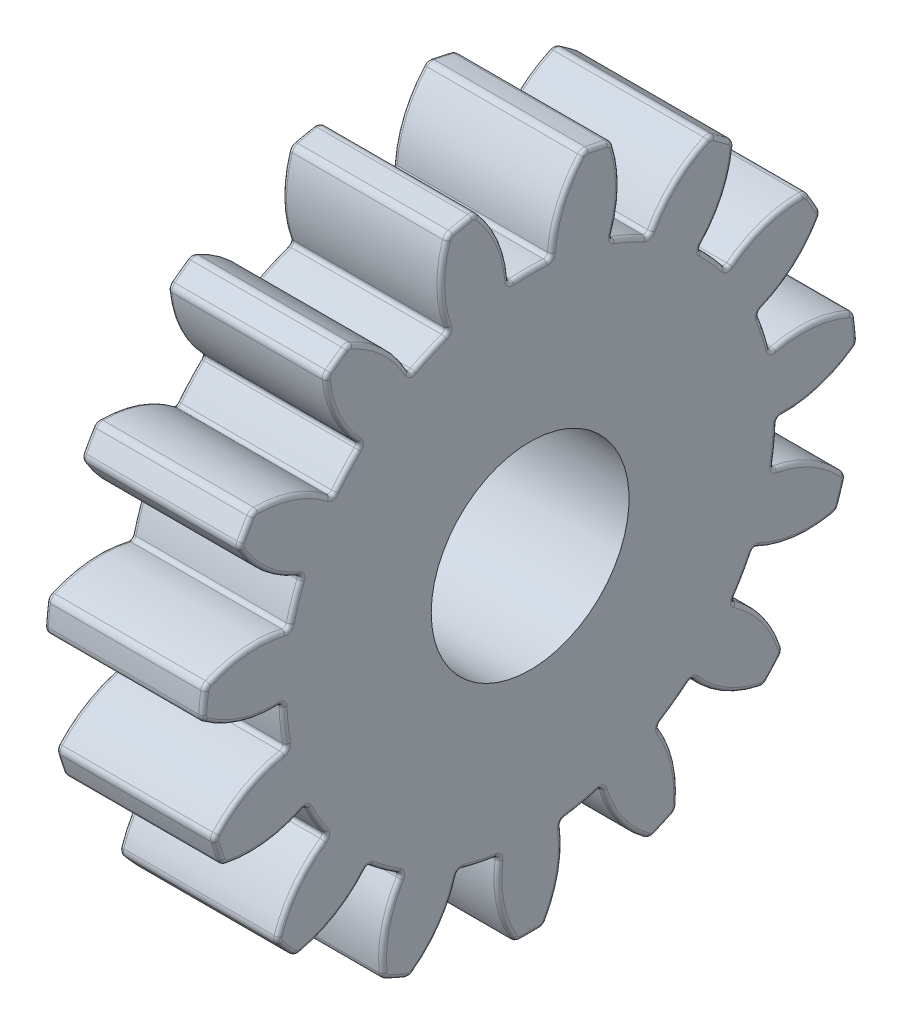
SolidWorks part; units mm, degrees
ref_plane "Plane1" through (0, 0, 0) normal (0, 0, 1) x (1, 0, 0)
ref_plane "Plane2" through (0, 0, 0) normal (0, 1, 0) x (1, 0, 0)
ref_plane "Plane3" through (0, 0, 0) normal (1, 0, 0) x (0, 0, -1)
sketch "HoldingSke" plane through (0, 0, 0) normal (0, 1, 0) x (1, 0, 0)
  line L0 (0, 0) -> (0.9659, -0.2588)
  line L1 (-15, 0) -> (100, 0) construction
  line L2 (0, 0) -> (-2.1039, 2.3779)
  line L3 (0, 0) -> (-11.863, 4.5341)
  line L4 (0, 0) -> (8.3417, 2.2352)
  line L5 (0, 0) -> (-46.8476, -17.4728)
  line L6 (0, 0) -> (-3.3159, -2.2372)
  line L7 (-2.1039, 2.3779) -> (8.6586, 51.2059)
  line L8 (-76.2, 54.61) -> (-75.3, 54.61)
  line L9 (-71.009, 38.7566) -> (-53.1078, 45.2721)
  line L10 (-76.2, 71.12) -> (104.1128, 71.12)
  line L11 (0, 0) -> (-4, 0)
  line L12 (-76.2, 101.6) -> (-76.162, 101.6)
  line L13 (24.9733, 27.94) -> (52.9518, 28.4284)
  line L14 (24.9733, 27.94) -> (24.9743, 27.94)
  line L15 (24.9733, 27.94) -> (100.4006, 29.5858)
  line L16 (-63.627, -1) -> (-12.827, -1)
  circle A0 centre (0, 0) radius 2.5
  circle A1 centre (0, 0) radius 6.249
  circle A2 centre (0, 0) radius 37.5
  circle A3 centre (0, 0) radius 2.5
  dimension "MHD" = 12.498
  dimension "Hub_dia" = 75
  dimension "Bore" = 5
  dimension "MBD" = 5
  dimension "Num_teeth" = 15
  dimension "Pitch" = 1
  dimension "Overall_len" = 50
  dimension "Show_teeth" = 15
  dimension "Thickness" = 4
  dimension "OAL" = 50.0001
  dimension "T_dim" = 0.9
  dimension "Ap" = 20
  dimension "H" = 19.05
  dimension "Pitch_radius" = 180.3128
  dimension "Width" = 4
  dimension "Backlash" = 0.038
  dimension "Addendum_fac" = 1
  dimension "Dedendum_fac" = 1.25
  dimension "Clearance_fac" = 0.25
  dimension "Dedendum_add" = 0.001
  dimension "Module" = 1
sketch "BasProSke" plane through (0, 0, 0) normal (0, 1, 0) x (1, 0, 0)
  line L0 (-10, 0) -> (60, 0) construction
  line L1 (0, 0) -> (0, 8.5)
  line L2 (0, 0) -> (4, 0)
  line L3 (4, 0) -> (4, 8.5)
  line L4 (4, 8.5) -> (0, 8.5)
  dimension "Thickness" = 4
  dimension "Diameter" = 17
revolve "Base-Revolve" add sketch "BasProSke" angle 360 about L0
sketch "TooCutSke" plane through (0, 0, 0) normal (1, 0, 0) x (0, 0, -1)
  line L1 (0, 0) -> (0, 107) construction
  line L2 (0, 0) -> (-0.8504, 7.4516) construction
  line L3 (0, 0) -> (-3.1044, 14.6049) construction
  line L4 (-0.8504, 7.4516) -> (-1.5522, 7.3025) construction
  arc A0 (0.5316, 6.2263) -> (-0.5316, 6.2263) centre (0, 0) ccw
  arc A1 (1.5766, 8.3784) -> (-1.5766, 8.3784) centre (0, 0) ccw
  circle A2 centre (0, 0) radius 7.5 construction
  circle A3 centre (0, 0) radius 7.0477 construction
  arc A4 (-0.5316, 6.2263) -> (-1.5766, 8.3784) centre (-3.5289, 6.1005) ccw
  arc A5 (1.5766, 8.3784) -> (0.5316, 6.2263) centre (3.5289, 6.1005) ccw
  dimension "Root_dia" = 12.498
  dimension "Overcut_dia" = 17.0508
  dimension "Pitch_dia" = 15
  dimension "Base_dia" = 14.0954
  dimension "Flank_rad" = 3
  dimension "Half_ang" = 12
  dimension "Half_CT" = 0.7175
extrude "ToothCut" cut sketch "TooCutSke" along normal through all
fillet "Breaks" [suppressed] radius 0.02
fillet "RootFillets" [suppressed] radius 0.251
pattern_circular "TeethCuts" count 15 every 24 about axis through (-10, 0, 0) along (1, 0, 0) of "ToothCut", "RootFillets", "Breaks"
sketch "HubNeaOneSke" plane through (0, 0, 0) normal (-1, 0, 0) x (0, 0, 1)
  circle A0 centre (0, 0) radius 6.249
  dimension "Diameter" = 12.498
extrude "HubNearOne" [suppressed] add sketch "HubNeaOneSke" along normal blind 46.0001
sketch "HubNeaBotSke" plane through (0, 0, 0) normal (-1, 0, 0) x (0, 0, 1)
  circle A0 centre (0, 0) radius 6.249
  dimension "Diameter" = 12.498
extrude "HubNearBoth" [suppressed] add sketch "HubNeaBotSke" along normal blind 23
ref_plane "FarPln" through (4, 0, 0) normal (1, 0, 0) x (0, 0, -1)
sketch "HubFarSke" plane through (4, 0, 0) normal (1, 0, 0) x (0, 0, -1)
  circle A0 centre (0, 0) radius 6.249
  dimension "Diameter" = 12.498
extrude "HubFar" [suppressed] add sketch "HubFarSke" along normal blind 23
sketch "BorSke" plane through (0, 0, 0) normal (1, 0, 0) x (0, 0, -1)
  circle A0 centre (0, 0) radius 2.5
  dimension "Diameter" = 5
extrude "Bore" cut sketch "BorSke" along normal mid plane 100.0001
sketch "KeySke" plane through (0, 0, 0) normal (1, 0, 0) x (0, 0, -1)
  line L0 (-1, 0) -> (-1, 3.4)
  line L1 (-1, 3.4) -> (1, 3.4)
  line L2 (1, 3.4) -> (1, 0)
  line L3 (0, 0) -> (0, 34) construction
  line L4 (-1, 0) -> (1, 0)
  dimension "Offset" = 3.4
  dimension "Width" = 2
extrude "Keyway" [suppressed] cut sketch "KeySke" along normal mid plane 100.0001
pattern_circular "Keyway2" [suppressed] count 2 every 90 about axis through (-10, 0, 0) along (1, 0, 0)
sketch "Sketch1" plane through (4, 0, 0) normal (1, 0, 0) x (0, 0, -1)
  circle A0 centre (0, 0) radius 8.3
  dimension "D1" = 16.6
extrude "Cut-Extrude1" cut sketch "Sketch1" against normal blind 10 flip side to cut
fillet "Fillet1" radius 0.2 30 edges at (2, -7.429, 3.7014) (2, -5.2812, 6.403) (2, -2.9046, 7.7752) (2, -5.8159, 5.9216) (2, -7.7216, 3.0441) (2, -8.2922, -0.3598) (2, -8.2922, 0.3598) (2, -7.7216, -3.0441) (2, -7.429, -3.7014) (2, -5.8159, -5.9216) (2, -5.2812, -6.403) (2, -2.9046, -7.7752) (2, -2.2203, -7.9975) (2, 0.509, -8.2844) (2, 1.2246, -8.2092) (2, 6.92, -4.583) (2, 6.4971, -5.1651) (2, 3.8345, -7.3611) (2, 4.4577, -7.0014) (2, -2.2203, 7.9975) (2, 0.509, 8.2844) (2, 1.2246, 8.2092) (2, 3.8345, 7.3611) (2, 4.4577, 7.0014) (2, 6.4971, 5.1651) (2, 6.92, 4.583) (2, 8.0362, 2.0759) (2, 8.1858, 1.3722) (2, 8.1858, -1.3722) (2, 8.0362, -2.0759)
fillet "Fillet2" radius 0.1 80 edges at (4, -3.1245, 5.4118) (0, 0.5193, -8.2589) (0, 0.8676, -8.2545) (0, 1.2092, -8.1864) (4, 0.8676, -8.2545) (0, 2.9482, -6.6457) (0, 3.8336, -7.3336) (0, 4.4343, -6.9868) (4, 3.8336, -7.3336) (4, 4.15, -7.188) (4, 4.4343, -6.9868) (4, 6.485, -5.1404) (0, 6.9115, -2.2559) (0, 8.0151, -2.0583) (0, 8.1186, -1.7257) (4, 6.9115, -2.2559) (4, 8.1186, -1.7257) (0, 8.1593, 1.3797) (0, 8.0151, 2.0583) (4, 8.1593, 1.3797) (4, 6.3011, 3.6267) (4, -1.5021, -7.1135) (4, -2.5648, -7.8938) (0, -2.2251, -7.9704) (0, -2.5648, -7.8938) (4, -5.2746, -6.3763) (4, -5.7901, -5.9122) (4, -6.2914, -3.6436) (0, -7.412, -3.6797) (0, -7.6942, -3.046) (4, -8.2679, -0.3468) (0, -8.3, 0) (4, -6.9175, 2.2374) (4, -7.6942, 3.046) (0, -7.5824, 3.3759) (0, -7.412, 3.6797) (0, -1.5021, 7.1135) (0, -2.2251, 7.9704) (0, -2.8848, 7.7561) (4, -1.5021, 7.1135) (4, -2.5648, 7.8938) (0, 0.5193, 8.2589) (4, 1.2092, 8.1864) (0, 4.15, 7.188) (4, 4.4343, 6.9868) (4, 3.8336, 7.3336) (0, 6.7148, -4.8786) (0, 6.8927, 4.5791) (4, -0.6532, 6.2148) (2, -1.1795, 6.1367) (4, -6.1124, 1.2992) (0, -6.1124, 1.2992) (2, -4.7248, 4.0898) (4, -5.0555, 3.6731) (0, -5.0555, 3.6731) (4, -6.1124, -1.2992) (2, -5.3497, -3.2297) (4, -5.0555, -3.6731) (2, -3.5735, -5.1264) (4, -3.1245, -5.4118) (0, -3.1245, -5.4118) (4, 6.249, 0) (2, 6.2263, 0.5316) (0, 4.1814, 4.6439) (2, 5.4718, 3.0181) (2, 1.4185, -6.0859) (0, 1.5211, -7.1094) (4, 1.5211, -7.1094) (0, 4.2813, -5.8761) (4, 4.2813, -5.8761) (2, 5.4718, -3.0181) (0, 6.3011, -3.6267) (4, 6.9115, 2.2559) (0, -2.966, -6.6378) (0, -5.4094, -4.8576) (2, -6.2008, 0.7746) (4, -7.2295, 0.7696) (2, -5.3497, 3.2297) (2, -2.6528, 5.658) (4, -2.966, 6.6378)
equation "' \"Module@HoldingSke\" = 6.35"
equation "' \"Num_teeth@HoldingSke\" = 12"
equation "' \"Ap@HoldingSke\" =  20"
equation "' \"Ap@HoldingSke\" = 20"
equation "' \"Width@HoldingSke\" = 0.5 * 25.4"
equation "' \"Hub_dia@HoldingSke\"= 1 * 25.4"
equation "' \"Hub_dia@HoldingSke\" = 1 * 25.4"
equation "' \"Overall_len@HoldingSke\" = 1.0 * 25.4"
equation "' \"Bore@HoldingSke\" = 0.75 * 25.4"
equation "' \"T_dim@HoldingSke\" = 0.1 * 25.4"
equation "' \"Width@KeySke\" = 0.25 * 25.4"
equation "' \"Show_teeth@HoldingSke\" = 13"
equation "' \"Backlash@HoldingSke\" = 0.009 * 25.4"
equation "' \"Addendum_fac@HoldingSke\" = 1.0"
equation "' \"Dedendum_fac@HoldingSke\" = 1.25"
equation "' \"Dedendum_add@HoldingSke\" = 0.00005 * 25.4"
equation "' \"Clearance_fac@HoldingSke\" = 0.25"
equation "\"Pitch@HoldingSke\" = 1 / \"Module@HoldingSke\""
equation "\"Overcut_dia@TooCutSke\" = (\"Num_teeth@HoldingSke\" + 2 * \"Addendum_fac@HoldingSke\") / \"Pitch@HoldingSke\" + 0.002 * 25.4"
equation "\"Pitch_dia@TooCutSke\" = \"Num_teeth@HoldingSke\" / \"Pitch@HoldingSke\""
equation "\"Base_dia@TooCutSke\" = \"Num_teeth@HoldingSke\" / \"Pitch@HoldingSke\" * cos((\"Ap@HoldingSke\"  * 3.14159265 / 180))"
equation "\"Root_dia@TooCutSke\" = (\"Num_teeth@HoldingSke\" + 2) / \"Pitch@HoldingSke\" - 2 * (\"Addendum_fac@HoldingSke\" + \"Dedendum_fac@HoldingSke\") / \"Pitch@HoldingSke\" - \"Dedendum_add@HoldingSke\" * 2"
equation "\"Half_ang@TooCutSke\" = 180 / \"Num_teeth@HoldingSke\""
equation "\"Half_CT@TooCutSke\" = \"Num_teeth@HoldingSke\" / \"Pitch@HoldingSke\" * sin((3.14159265 / 2 / \"Num_teeth@HoldingSke\")) / 2 - 7 * \"Backlash@HoldingSke\" / 4"
equation "\"Flank_rad@TooCutSke\" = \"Num_teeth@HoldingSke\" / \"Pitch@HoldingSke\" / 5"
equation "\"Radius@RootFillets\" = \"Clearance_fac@HoldingSke\" / \"Pitch@HoldingSke\" + \"Dedendum_add@HoldingSke\""
equation "\"Break_rad@Breaks\" = 0.02 / \"Pitch@HoldingSke\""
equation "\"Thickness@HoldingSke\" = \"Width@HoldingSke\""
equation "\"OAL@HoldingSke\" = \"Thickness@HoldingSke\""
equation "\"MHD@HoldingSke\" = (\"Num_teeth@HoldingSke\" + 2) / \"Pitch@HoldingSke\" - 2 * (\"Addendum_fac@HoldingSke\" + \"Dedendum_fac@HoldingSke\")  / \"Pitch@HoldingSke\" - \"Dedendum_add@HoldingSke\" * 2"
equation "\"MBD@HoldingSke\" = (\"Num_teeth@HoldingSke\" + 2) / \"Pitch@HoldingSke\" - 2 * (\"Addendum_fac@HoldingSke\" + \"Dedendum_fac@HoldingSke\")  / \"Pitch@HoldingSke\" - \"Dedendum_add@HoldingSke\" * 2 - 0.002 * 25.4"
equation "\"MHD@HoldingSke\" = ((sgn( \"MHD@HoldingSke\" - \"Hub_dia@HoldingSke\" )-1)*( \"MHD@HoldingSke\" - \"Hub_dia@HoldingSke\" ))/-2+ \"Hub_dia@HoldingSke\""
equation "\"MBD@HoldingSke\" = ((sgn( \"MBD@HoldingSke\" - \"Bore@HoldingSke\" )-1)*( \"MBD@HoldingSke\" - \"Bore@HoldingSke\" ))/-2+ \"Bore@HoldingSke\""
equation "\"OAL@HoldingSke\" = ((sgn( \"OAL@HoldingSke\" - \"Overall_len@HoldingSke\" )+1)*( \"OAL@HoldingSke\" - \"Overall_len@HoldingSke\" ))/2 + \"Overall_len@HoldingSke\" + 0.000002 * 25.4"
equation "\"Num_teeth@TeethCuts\" = int( \"Show_teeth@HoldingSke\" ) + 1"
equation "\"Num_teeth@TeethCuts\" = ((sgn( \"Num_teeth@TeethCuts\" - \"Num_teeth@HoldingSke\" )-1)*( \"Num_teeth@TeethCuts\" - \"Num_teeth@HoldingSke\" ))/-2+ \"Num_teeth@HoldingSke\""
equation "\"Num_teeth@TeethCuts\" = ((sgn( \"Num_teeth@TeethCuts\" - 2.0)+1)*( \"Num_teeth@TeethCuts\" - 2.0))/2 +2.0"
equation "\"Angle@TeethCuts\" = 360.0 / \"Num_teeth@HoldingSke\""
equation "\"Diameter@BasProSke\" = (\"Num_teeth@HoldingSke\" + 2 * \"Addendum_fac@HoldingSke\") / \"Pitch@HoldingSke\""
equation "\"Thickness@BasProSke\"  = \"Thickness@HoldingSke\""
equation "' \"Fillet_rad@BasProSke\" =  \"Thickness@HoldingSke\" * 0.05"
equation "' \"Fillet_rad@BasProSke\" = \"Thickness@HoldingSke\" * 0.05"
equation "\"MHD@HoldingSke\" = ((sgn( \"MHD@HoldingSke\" - \"Root_dia@TooCutSke\" )-1)*( \"MHD@HoldingSke\" - \"Root_dia@TooCutSke\" ))/-2+ \"Root_dia@TooCutSke\""
equation "\"Diameter@HubNeaOneSke\" = \"MHD@HoldingSke\""
equation "\"Length@HubNearOne\" = \"OAL@HoldingSke\" - \"Thickness@BasProSke\""
equation "\"Diameter@HubNeaBotSke\" = \"MHD@HoldingSke\""
equation "\"Length@HubNearBoth\" = ( \"OAL@HoldingSke\" - \"Thickness@BasProSke\" ) / 2.0"
equation "\"Thickness@FarPln\" = \"Thickness@BasProSke\""
equation "\"Diameter@HubFarSke\" = \"MHD@HoldingSke\""
equation "\"Length@HubFar\" = ( \"OAL@HoldingSke\" - \"Thickness@BasProSke\" ) / 2.0"
equation "\"Diameter@BorSke\" = \"MBD@HoldingSke\""
equation "\"D1@Bore\" = \"OAL@HoldingSke\" * 2.0"
equation "\"D1@Keyway\" = \"OAL@HoldingSke\" * 2.0"
equation "\"Offset@KeySke\" = \"T_dim@HoldingSke\" + \"MBD@HoldingSke\" / 2.0"
